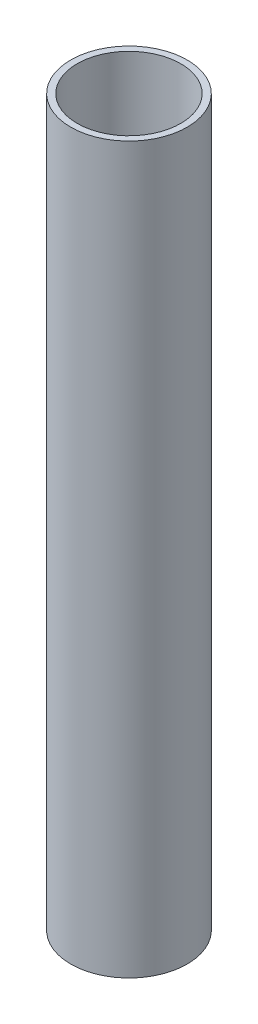
SolidWorks part; units mm, degrees
ref_plane "Front Plane" through (0, 0, 0) normal (0, 0, 1) x (1, 0, 0)
ref_plane "Top Plane" through (0, 0, 0) normal (0, 1, 0) x (1, 0, 0)
ref_plane "Right Plane" through (0, 0, 0) normal (1, 0, 0) x (0, 0, -1)
sketch "Sketch1" plane through (0, 0, 0) normal (0, 1, 0) x (1, 0, 0)
  circle A0 centre (0, 0) radius 57.15
  circle A1 centre (0, 0) radius 50.8
  dimension "D1" = 114.3
  dimension "D2" = 101.6
extrude "Boss-Extrude1" add sketch "Sketch1" along normal blind 711.2
